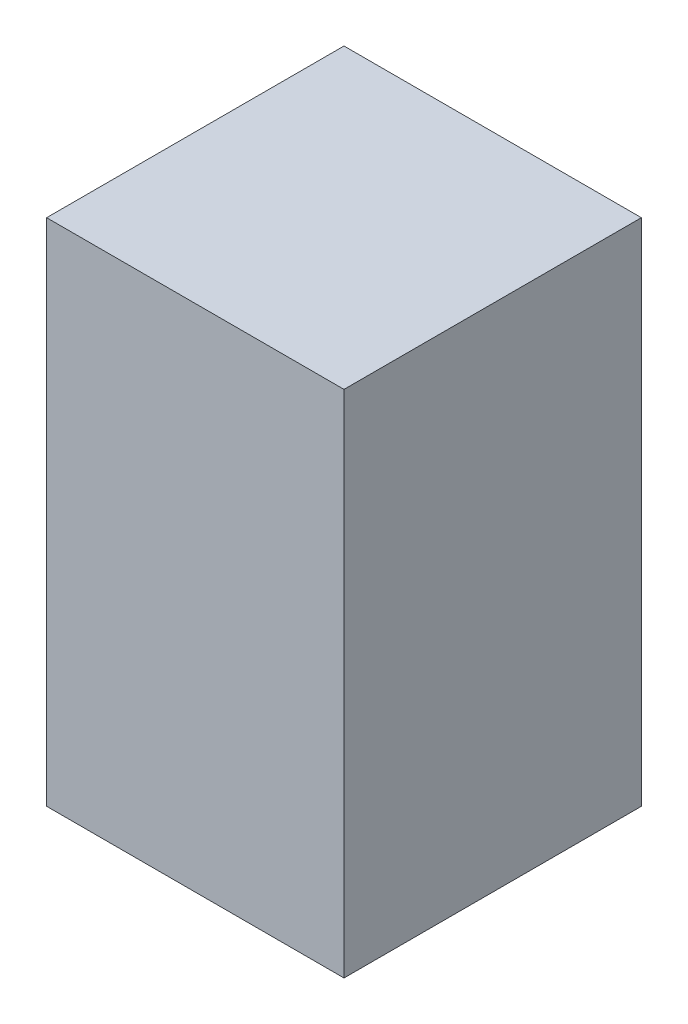
SolidWorks part; units mm, degrees
ref_plane "Alzado" through (0, 0, 0) normal (0, 0, 1) x (1, 0, 0)
ref_plane "Planta" through (0, 0, 0) normal (0, 1, 0) x (1, 0, 0)
ref_plane "Vista lateral" through (0, 0, 0) normal (1, 0, 0) x (0, 0, -1)
sketch "Croquis1" plane through (0, 0, 0) normal (0, 1, 0) x (1, 0, 0)
  line L1 (-350, -350) -> (350, -350)
  line L2 (-350, -350) -> (-350, 350)
  line L3 (-350, 350) -> (350, 350)
  line L4 (350, -350) -> (350, 350)
  line L5 (-350, -350) -> (350, 350) construction
  line L6 (-350, 350) -> (350, -350) construction
  point P0 (0, 0)
  dimension "D1" = 700
  dimension "D2" = 700
extrude "Saliente-Extruir1" add sketch "Croquis1" along normal blind 1200
